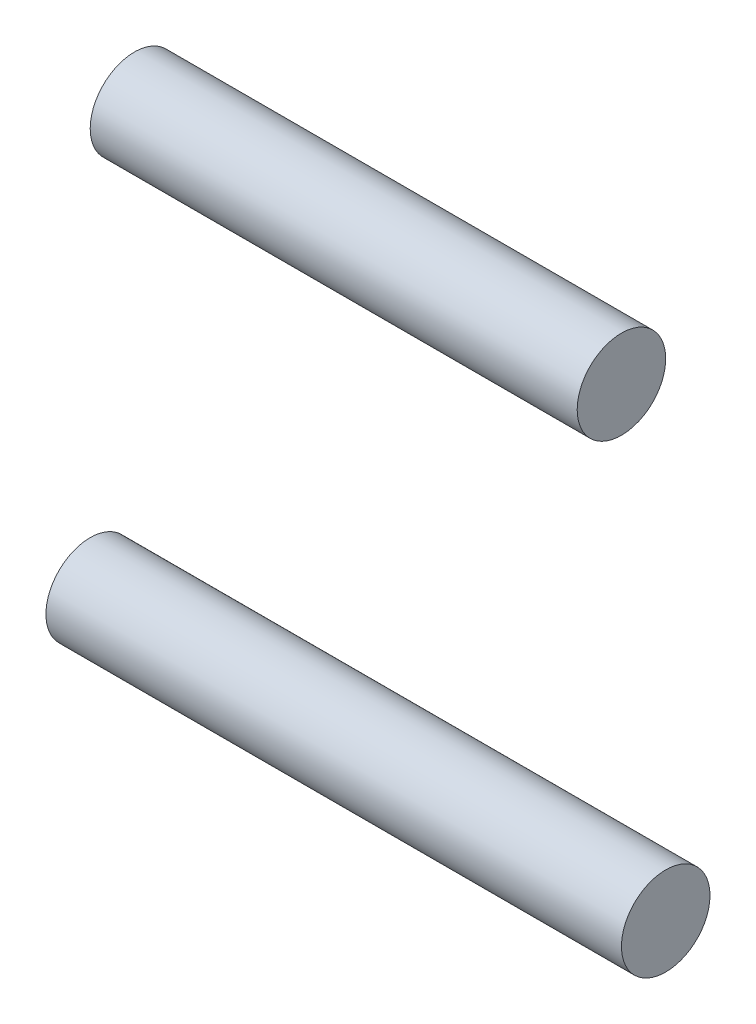
SolidWorks part; units mm, degrees
ref_plane "Płaszczyzna przednia" through (0, 0, 0) normal (0, 0, 1) x (1, 0, 0)
ref_plane "Płaszczyzna górna" through (0, 0, 0) normal (0, 1, 0) x (1, 0, 0)
ref_plane "Płaszczyzna prawa" through (0, 0, 0) normal (1, 0, 0) x (0, 0, -1)
sketch "Szkic1" plane through (0, 0, 0) normal (0, 0, 1) x (1, 0, 0)
  line L0 (45, 0) -> (175, 0)
  line L2 (165, 100) -> (55, 100)
  point P2 (0, 0)
sweep "Wyciągnięcie po ścieżce1" add path "Szkic1" circular profile diameter 20 parameters "D3"=20
sketch "Szkic6" plane through (0, 0, 0) normal (0, 0, 1) x (1, 0, 0)
  line L0 (45, 0) -> (175, 0)
sweep "Wyciągnięcie po ścieżce2" add path "Szkic6" circular profile diameter 20 parameters "D3"=20
